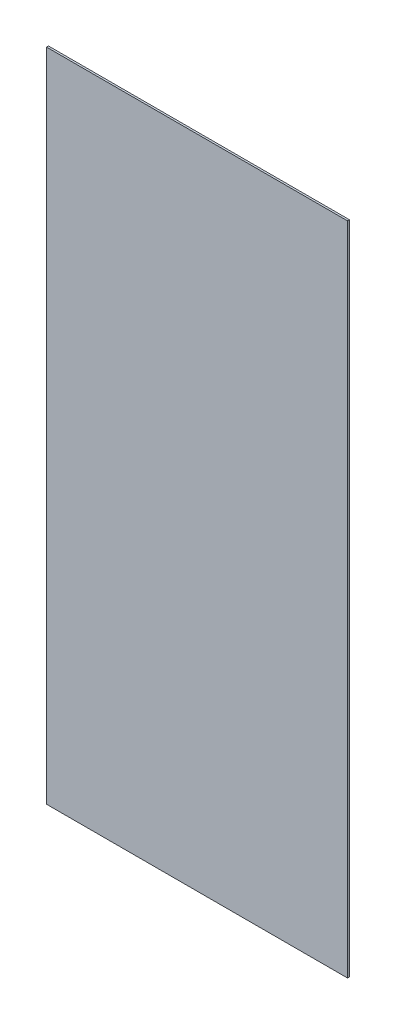
SolidWorks part; units mm, degrees
material "Perspex (TM) GS arkusz akrylowy"
ref_plane "Płaszczyzna przednia" through (0, 0, 0) normal (0, 0, 1) x (1, 0, 0)
ref_plane "Płaszczyzna górna" through (0, 0, 0) normal (0, 1, 0) x (1, 0, 0)
ref_plane "Płaszczyzna prawa" through (0, 0, 0) normal (1, 0, 0) x (0, 0, -1)
sketch "Szkic1" plane through (0, 0, 0) normal (0, 0, 1) x (1, 0, 0)
  line L1 (0, 0) -> (780, 0)
  line L2 (0, 0) -> (0, 1700)
  line L3 (0, 1700) -> (780, 1700)
  line L4 (780, 0) -> (780, 1700)
  dimension "D1" = 780
  dimension "D2" = 1700
extrude "Dodanie-wyciągnięcie1" add sketch "Szkic1" along normal blind 5 contours L3 L4 L1 L2
